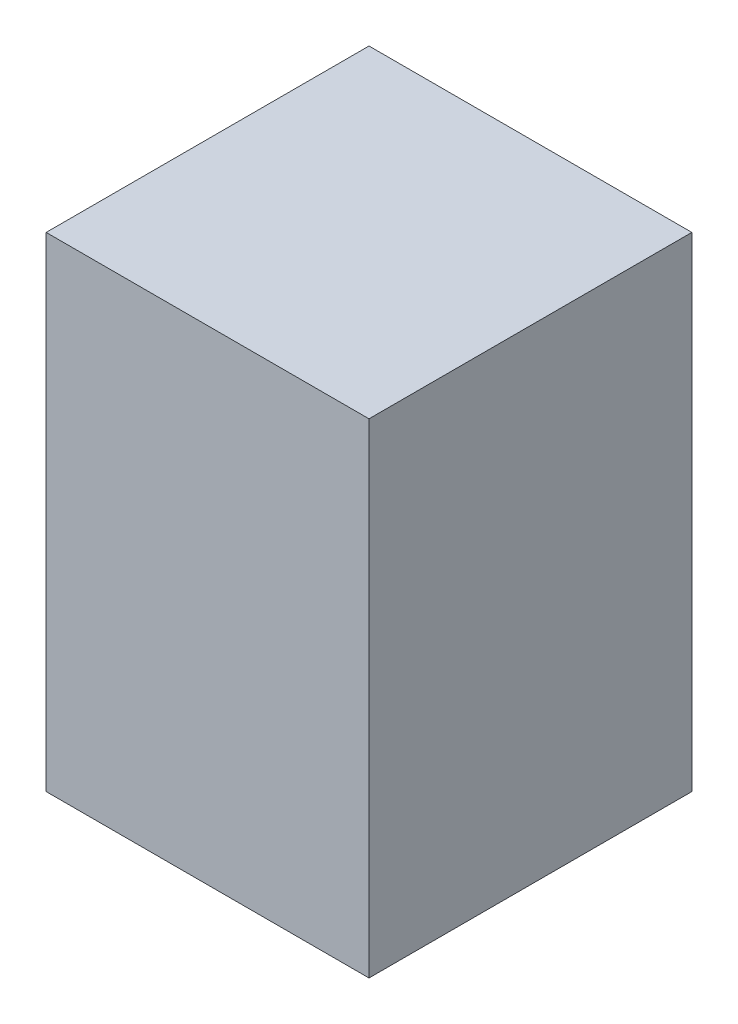
SolidWorks part; units mm, degrees
ref_plane "Front Plane" through (0, 0, 0) normal (0, 0, 1) x (1, 0, 0)
ref_plane "Top Plane" through (0, 0, 0) normal (0, 1, 0) x (1, 0, 0)
ref_plane "Right Plane" through (0, 0, 0) normal (1, 0, 0) x (0, 0, -1)
other "Configuration Table"
sketch "Sketch1" plane through (0, 0, 0) normal (0, 0, 1) x (1, 0, 0)
  line L1 (1260, 0) -> (1340, 0)
  line L2 (1260, 0) -> (1260, 120)
  line L3 (1260, 120) -> (1340, 120)
  line L4 (1340, 0) -> (1340, 120)
extrude "STORE_ayak_4_1" add sketch "Sketch1" against normal blind 80 from offset 680 separate body
